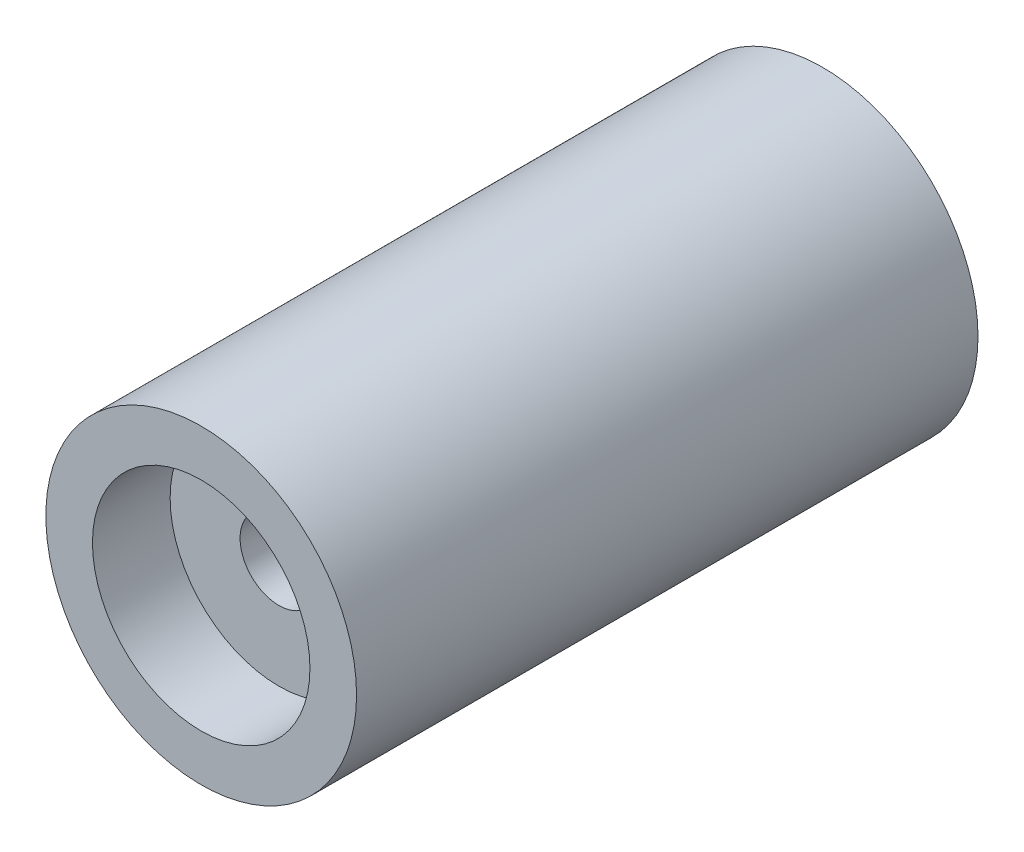
SolidWorks part; units mm, degrees
ref_plane "前视基准面" through (0, 0, 0) normal (0, 0, 1) x (1, 0, 0)
ref_plane "上视基准面" through (0, 0, 0) normal (0, 1, 0) x (1, 0, 0)
ref_plane "右视基准面" through (0, 0, 0) normal (1, 0, 0) x (0, 0, -1)
sketch "草图1" plane through (0, 0, 0) normal (0, 0, 1) x (1, 0, 0)
  circle A0 centre (0, 0) radius 10
  circle A1 centre (0, 0) radius 2.5
  dimension "D1" = 20
extrude "凸台-拉伸1" add sketch "草图1" along normal blind 40
ref_plane "基准面1" through (0, 0, 20) normal (0, 0, 1) x (1, 0, 0)
sketch "草图2" plane through (0, 0, 0) normal (0, 0, -1) x (-1, 0, 0)
  circle A0 centre (0, 0) radius 7
  dimension "D1" = 14
extrude "切除-拉伸1" cut sketch "草图2" against normal blind 5
mirror "镜向1" about plane through (0, 0, 20) normal (0, 0, 1) of "切除-拉伸1"
